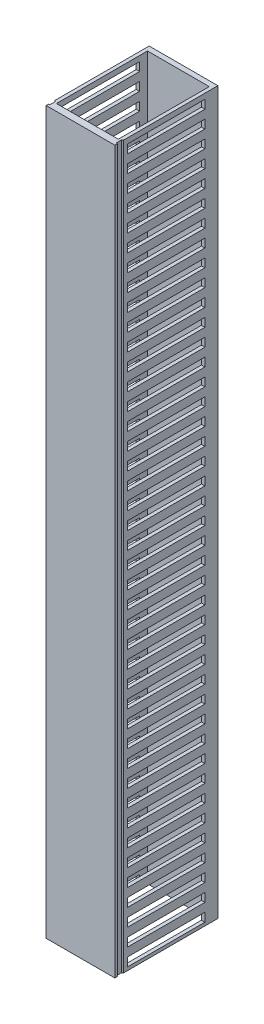
SolidWorks part; units mm, degrees
ref_plane "Front" through (0, 0, 0) normal (0, 0, 1) x (1, 0, 0)
ref_plane "Top" through (0, 0, 0) normal (0, 1, 0) x (1, 0, 0)
ref_plane "Right" through (0, 0, 0) normal (1, 0, 0) x (0, 0, -1)
sketch "Sketch1" plane through (0, 0, 0) normal (0, 1, 0) x (1, 0, 0)
  line L1 (0, 0) -> (40, 0)
  line L2 (0, 0) -> (0, 60)
  line L3 (0, 60) -> (40, 60)
  line L4 (40, 0) -> (40, 60)
extrude "Boss-Extrude1" add sketch "Sketch1" along normal blind 420
sketch "Sketch2" plane through (0, 0, 0) normal (0, -1, 0) x (1, 0, 0)
  line L0 (-1.6841, -1.4562) -> (0.6978, -1.4562)
  line L1 (0.6978, -1.4562) -> (0.6978, -4.5643)
  line L2 (0.6978, -4.5643) -> (-2.0327, -6.772)
  line L3 (-2.0327, -6.772) -> (-1.6841, -1.4562)
  line L4 (20, 0) -> (20, 4.9054) construction
  line L5 (0, 0) -> (40, 0) construction
  line L6 (42.0327, -6.772) -> (41.6841, -1.4562)
  line L7 (39.3022, -4.5643) -> (42.0327, -6.772)
  line L8 (39.3022, -1.4562) -> (39.3022, -4.5643)
  line L9 (41.6841, -1.4562) -> (39.3022, -1.4562)
extrude "Cut-Extrude1" cut sketch "Sketch2" against normal through all
sketch "Sketch3" plane through (0, 0, 0) normal (-1, 0, 0) x (0, 0, 1)
  line L1 (-7.4463, 416.9095) -> (-52.4463, 416.9095)
  line L2 (-7.4463, 416.9095) -> (-7.4463, 411.9095)
  line L3 (-7.4463, 411.9095) -> (-52.4463, 411.9095)
  line L4 (-52.4463, 416.9095) -> (-52.4463, 411.9095)
  dimension "D1" = 5
  dimension "D2" = 45
extrude "Cut-Extrude2" cut sketch "Sketch3" against normal through all
sketch "Sketch4" plane through (0, 420, 0) normal (0, 1, 0) x (1, 0, 0)
  line L0 (40, 5.1285) -> (40, 60) construction
  line L1 (38, 4) -> (2, 4)
  line L2 (38, 4) -> (38, 57)
  line L3 (38, 57) -> (2, 57)
  line L4 (2, 4) -> (2, 57)
  line L5 (0, 60) -> (0, 5.1285) construction
  line L6 (0, 0) -> (40, 0) construction
  line L7 (40, 60) -> (0, 60) construction
  dimension "D1" = 2
  dimension "D2" = 2
  dimension "D3" = 4
  dimension "D4" = 3
extrude "Cut-Extrude3" cut sketch "Sketch4" against normal through all
pattern_linear "LPattern1" count 42 spacing 10 along (0, -1, 0) of "Cut-Extrude2"
